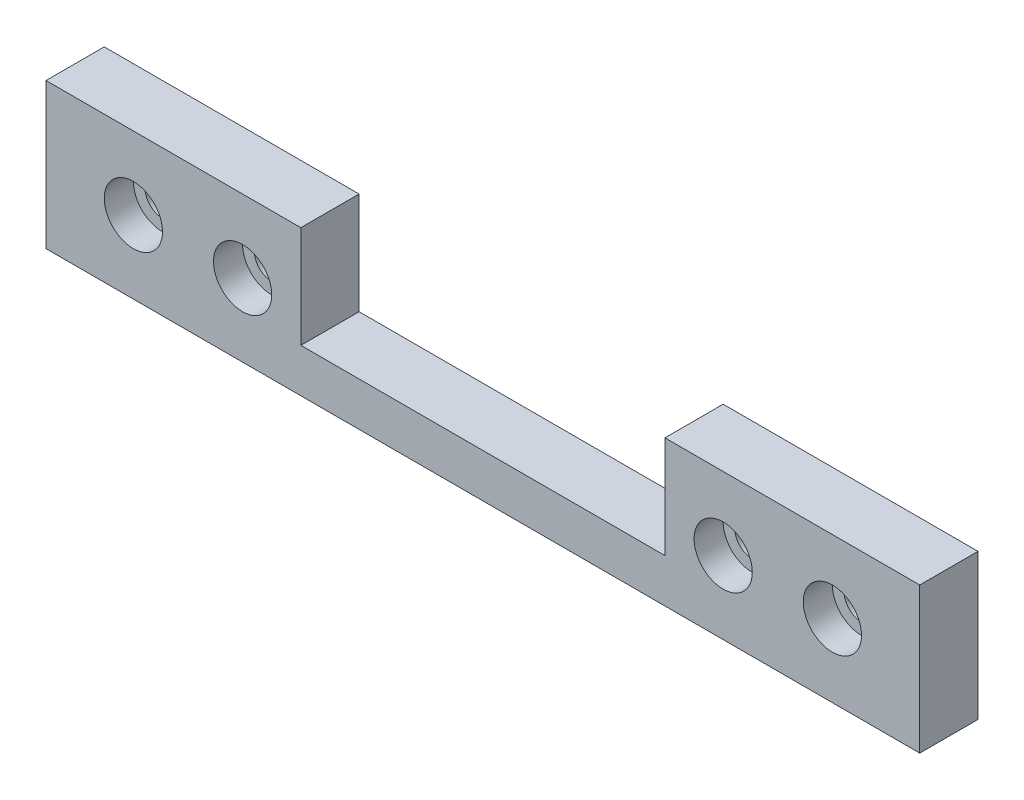
SolidWorks part; units mm, degrees
material "赛钢"
ref_plane "前基準面" through (0, 0, 0) normal (0, 0, 1) x (1, 0, 0)
ref_plane "上基準面" through (0, 0, 0) normal (0, 1, 0) x (1, 0, 0)
ref_plane "右基準面" through (0, 0, 0) normal (1, 0, 0) x (0, 0, -1)
sketch "草图1" plane through (0, 0, 0) normal (0, 0, 1) x (1, 0, 0)
  line L0 (60, 0) -> (60, 45.3693) construction
  line L1 (0, 0) -> (120, 0)
  line L2 (0, 0) -> (0, 20)
  line L3 (0, 20) -> (120, 20)
  line L4 (120, 0) -> (120, 20)
  dimension "D1" = 120
  dimension "D2" = 20
extrude "凸台-拉伸1" add sketch "草图1" along normal blind 8
sketch "草图2" plane through (0, 0, 8) normal (0, 0, 1) x (1, 0, 0)
  line L0 (120, 20) -> (0, 20) construction
  line L1 (85, 20) -> (35, 20)
  line L2 (85, 20) -> (85, 6)
  line L3 (85, 6) -> (35, 6)
  line L4 (35, 20) -> (35, 6)
  line L5 (60, 20) -> (60, 0) construction
  line L6 (0, 0) -> (120, 0) construction
  dimension "D1" = 14
  dimension "D2" = 50
extrude "切除-拉伸1" cut sketch "草图2" against normal through all
hole_wizard "M4 六角凹头螺钉的柱形沉头孔1" positions "草图4" profile "草图3" counterbore size "M4" standard "ISO" end condition through all
sketch "草图4" plane through (0, 0, 8) normal (0, 0, 1) x (1, 0, 0)
  line L0 (60, 0) -> (60, 6) construction
  line L1 (0, 0) -> (120, 0) construction
  line L2 (35, 6) -> (85, 6) construction
  line L3 (35, 20) -> (0, 20) construction
  point P0 (12, 10)
  point P1 (27, 10)
  point P3 (93, 10)
  point P5 (108, 10)
  dimension "D1" = 66
  dimension "D2" = 96
  dimension "D3" = 10
sketch "草图3" plane through (12, 10, 8) normal (1, 0, 0) x (0, -1, 0)
  line L0 (0, 0) -> (0, 8)
  line L1 (0, 8) -> (2.4, 8)
  line L3 (2.4, 8) -> (2.4, 4)
  line L4 (2.4, 4) -> (4, 4)
  line L5 (4, 4) -> (4, 0)
  line L7 (4, 0) -> (0, 0)
  line L11 (0, -6.35) -> (0, 107.95) construction
  dimension "通孔孔直径" = 4.8
  dimension "通孔孔深度" = 8
  dimension "柱形沉头孔直径" = 8
  dimension "柱形沉头孔深度" = 4
sketch "草图5" plane through (0, 0, 8) normal (0, 0, 1) x (1, 0, 0)
  line L0 (60, 0) -> (60, 6) construction
  line L1 (0, 0) -> (120, 0) construction
  line L2 (35, 6) -> (85, 6) construction
ref_plane "基准面1" through (60, 0, 0) normal (-1, 0, 0) x (0, 0, 1)
